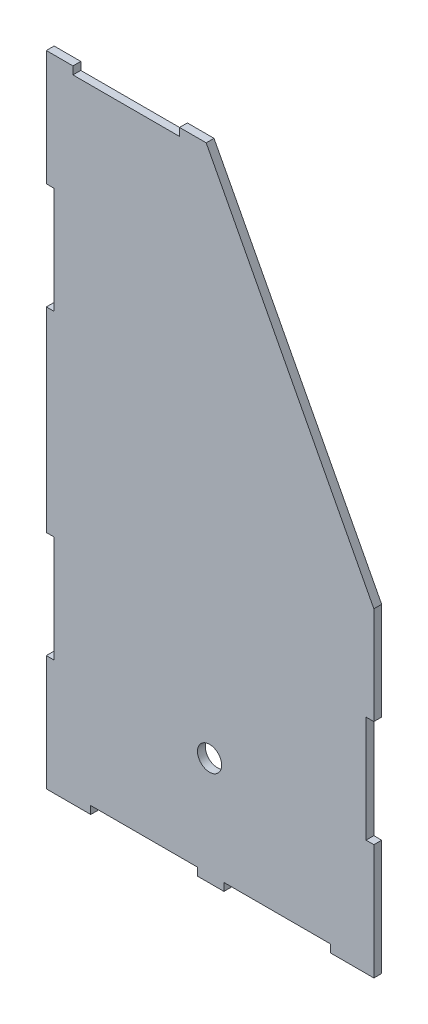
SolidWorks part; units mm, degrees
ref_plane "Front Plane" through (0, 0, 0) normal (0, 0, 1) x (1, 0, 0)
ref_plane "Top Plane" through (0, 0, 0) normal (0, 1, 0) x (1, 0, 0)
ref_plane "Right Plane" through (0, 0, 0) normal (1, 0, 0) x (0, 0, -1)
sketch "Sketch1" plane through (0, 0, 0) normal (0, 0, 1) x (1, 0, 0)
  line L0 (435.5199, 642.8699) -> (555.4079, 414.2699)
  line L1 (321.2199, 642.8699) -> (435.5199, 642.8699)
  line L2 (321.2199, 642.8699) -> (321.2199, 185.6699)
  line L3 (321.2199, 185.6699) -> (555.4079, 185.6699)
  line L4 (555.4079, 414.2699) -> (555.4079, 185.6699)
  dimension "D1" = 234.188
  dimension "D2" = 457.2
  dimension "D3" = 114.3
  dimension "D4" = 228.6
extrude "Boss-Extrude3" add sketch "Sketch1" along normal blind 5.588
sketch "Sketch2" plane through (0, 0, 5.588) normal (0, 0, 1) x (1, 0, 0)
  line L0 (326.8079, 642.8699) -> (326.8079, 185.6699) construction
  line L1 (435.5199, 642.8699) -> (321.2199, 642.8699) construction
  line L2 (321.2199, 185.6699) -> (555.4079, 185.6699) construction
  line L3 (321.2199, 191.2579) -> (555.4079, 191.2579) construction
  line L4 (321.2199, 642.8699) -> (321.2199, 185.6699) construction
  line L5 (555.4079, 185.6699) -> (555.4079, 414.2699) construction
  line L6 (321.2199, 637.2819) -> (438.4505, 637.2819) construction
  line L7 (549.8199, 185.6699) -> (549.8199, 424.9249) construction
  line L8 (555.4079, 414.2699) -> (435.5199, 642.8699) construction
  line L10 (416.4699, 642.8699) -> (340.2699, 642.8699)
  line L11 (416.4699, 642.8699) -> (416.4699, 637.2819)
  line L12 (416.4699, 637.2819) -> (340.2699, 637.2819)
  line L13 (340.2699, 642.8699) -> (340.2699, 637.2819)
  line L14 (321.2199, 560.3199) -> (326.8079, 560.3199)
  line L15 (321.2199, 560.3199) -> (321.2199, 484.1199)
  line L16 (321.2199, 484.1199) -> (326.8079, 484.1199)
  line L17 (326.8079, 560.3199) -> (326.8079, 484.1199)
  line L18 (321.2199, 344.4199) -> (326.8079, 344.4199)
  line L19 (321.2199, 344.4199) -> (321.2199, 268.2199)
  line L20 (321.2199, 268.2199) -> (326.8079, 268.2199)
  line L21 (326.8079, 344.4199) -> (326.8079, 268.2199)
  line L22 (352.9699, 191.2579) -> (429.1699, 191.2579)
  line L23 (352.9699, 191.2579) -> (352.9699, 185.6699)
  line L24 (352.9699, 185.6699) -> (429.1699, 185.6699)
  line L25 (429.1699, 191.2579) -> (429.1699, 185.6699)
  line L26 (448.2199, 191.2579) -> (524.4199, 191.2579)
  line L27 (448.2199, 191.2579) -> (448.2199, 185.6699)
  line L28 (448.2199, 185.6699) -> (524.4199, 185.6699)
  line L29 (524.4199, 191.2579) -> (524.4199, 185.6699)
  line L30 (549.8199, 344.4199) -> (555.4079, 344.4199)
  line L31 (549.8199, 344.4199) -> (549.8199, 268.2199)
  line L32 (549.8199, 268.2199) -> (555.4079, 268.2199)
  line L33 (555.4079, 344.4199) -> (555.4079, 268.2199)
  point P38 (552.6139, 268.2199)
  dimension "D1" = 5.588
  dimension "D2" = 5.588
  dimension "D3" = 5.588
  dimension "D4" = 5.588
  dimension "D6" = 76.2
  dimension "D8" = 82.55
  dimension "D9" = 82.55
  dimension "D5" = 19.05
  dimension "D10" = 76.2
  dimension "D11" = 76.2
  dimension "D12" = 19.05
  dimension "D14" = 82.55
  dimension "D7" = 76.2
  dimension "D13" = 31.75
extrude "Cut-Extrude1" cut sketch "Sketch2" against normal through all
sketch "Sketch3" plane through (0, 0, 0) normal (0, 0, 1) x (1, 0, 0)
  line L0 (429.1699, 185.6699) -> (448.2199, 185.6699) construction
  line L1 (555.4079, 185.6699) -> (555.4079, 268.2199) construction
  circle A0 centre (437.9329, 262.9891) radius 8.636
  dimension "D3" = 17.272
  dimension "D1" = 77.3192
  dimension "D2" = 117.475
extrude "Cut-Extrude3" cut sketch "Sketch3" against normal through all and the other way through all
equation "\"width\"= 9in"
equation "\"Height\"= 18in"
equation "\"D3@Sketch1\"=\"width\"/2"
equation "\"D4@Sketch1\"=\"Height\"/2"
equation "\"thick\"= 0.22"
equation "\"D1@Sketch2\"=\"thick\""
equation "\"D2@Sketch2\"=\"thick\""
equation "\"D3@Sketch2\"=\"thick\""
equation "\"D4@Sketch2\"=\"thick\""
equation "\"D2@Sketch1\"=\"Height\""
equation "\"D1@Sketch1\"= \"width\" + \"thick\""
equation "\"D1@Boss-Extrude3\"=\"thick\""
